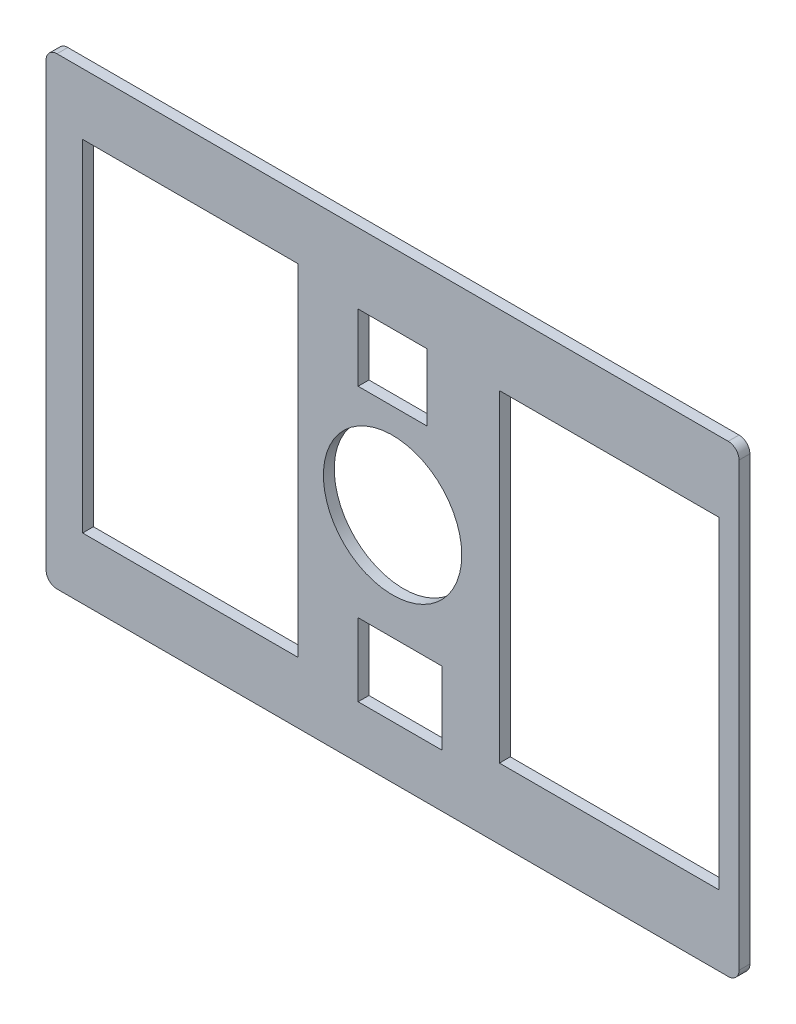
SolidWorks part; units mm, degrees
ref_plane "Front Plane" through (0, 0, 0) normal (0, 0, 1) x (1, 0, 0)
ref_plane "Top Plane" through (0, 0, 0) normal (0, 1, 0) x (1, 0, 0)
ref_plane "Right Plane" through (0, 0, 0) normal (1, 0, 0) x (0, 0, -1)
sketch "Sketch1" plane through (0, 0, 0) normal (0, 0, 1) x (1, 0, 0)
  line L1 (61.855, -42.715) -> (-61.855, -42.715)
  line L2 (63.855, -40.715) -> (63.855, 40.715)
  line L3 (61.855, 42.715) -> (-61.855, 42.715)
  line L4 (-63.855, -40.715) -> (-63.855, 40.715)
  line L5 (63.855, -42.715) -> (-63.855, 42.715) construction
  line L6 (63.855, 42.715) -> (-63.855, -42.715) construction
  line L7 (-17.405, -31.4153) -> (-57.129, -31.4153)
  line L8 (-17.405, -31.4153) -> (-17.405, 31.4153)
  line L9 (-17.405, 31.4153) -> (-57.129, 31.4153)
  line L10 (-57.129, -31.4153) -> (-57.129, 31.4153)
  line L11 (-17.405, -31.4153) -> (-57.129, 31.4153) construction
  line L12 (-17.405, 31.4153) -> (-57.129, -31.4153) construction
  line L13 (60.1691, -29.7289) -> (19.6957, -29.7289)
  line L14 (60.1691, -29.7289) -> (60.1691, 29.7289)
  line L15 (60.1691, 29.7289) -> (19.6957, 29.7289)
  line L16 (19.6957, -29.7289) -> (19.6957, 29.7289)
  line L17 (60.1691, -29.7289) -> (19.6957, 29.7289) construction
  line L18 (60.1691, 29.7289) -> (19.6957, -29.7289) construction
  line L19 (6.3498, 17.3944) -> (-6.3498, 17.3944)
  line L20 (6.3498, 17.3944) -> (6.3498, 29.7289)
  line L21 (6.3498, 29.7289) -> (-6.3498, 29.7289)
  line L22 (-6.3498, 17.3944) -> (-6.3498, 29.7289)
  line L23 (6.3498, 17.3944) -> (-6.3498, 29.7289) construction
  line L24 (6.3498, 29.7289) -> (-6.3498, 17.3944) construction
  line L25 (9.0767, -32.9613) -> (-6.3498, -32.9613)
  line L26 (9.0767, -32.9613) -> (9.0767, -19.5471)
  line L27 (9.0767, -19.5471) -> (-6.3498, -19.5471)
  line L28 (-6.3498, -32.9613) -> (-6.3498, -19.5471)
  line L29 (9.0767, -32.9613) -> (-6.3498, -19.5471) construction
  line L30 (9.0767, -19.5471) -> (-6.3498, -32.9613) construction
  circle A0 centre (0, 0) radius 12.75
  arc A1 (-63.855, 40.715) -> (-61.855, 42.715) centre (-61.855, 40.715) cw
  arc A2 (63.855, 40.715) -> (61.855, 42.715) centre (61.855, 40.715) ccw
  arc A3 (61.855, -42.715) -> (63.855, -40.715) centre (61.855, -40.715) ccw
  arc A4 (-61.855, -42.715) -> (-63.855, -40.715) centre (-61.855, -40.715) cw
  point P0 (0, 0)
  point P20 (-37.267, 0)
  point P25 (39.9324, 0)
  point P30 (0, 23.5616)
  point P35 (1.3635, -26.2542)
  dimension "D3" = 25.5
  dimension "D4" = 2
  dimension "D5" = 2
  dimension "D1" = 127.71
  dimension "D2" = 85.43
extrude "Boss-Extrude1" add sketch "Sketch1" along normal blind 2
